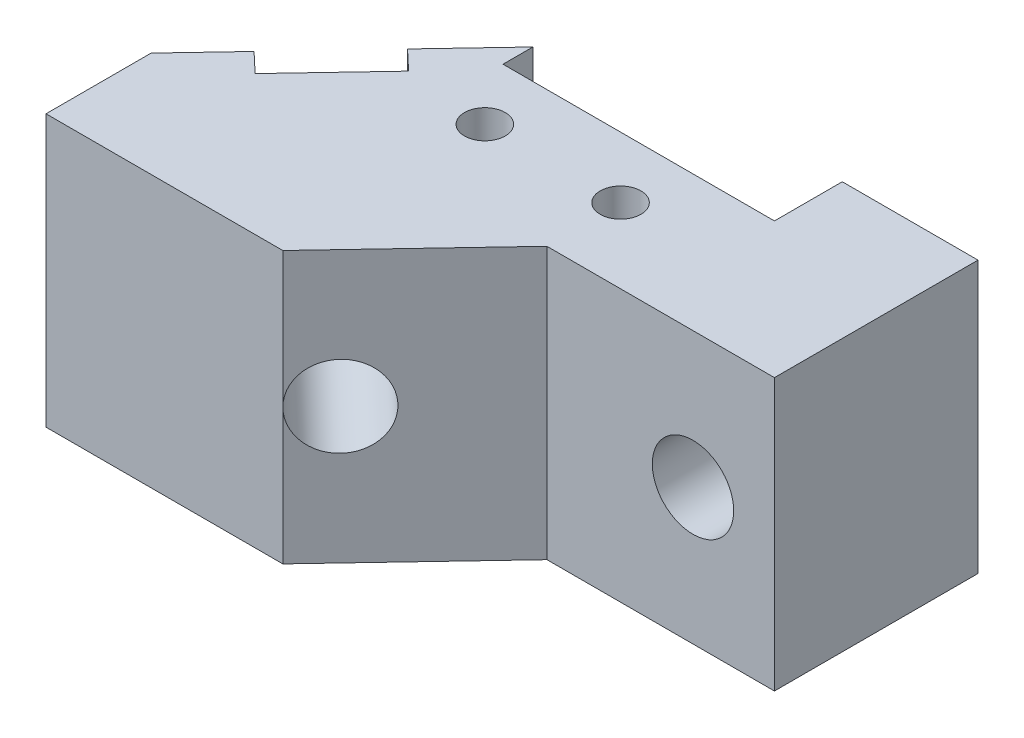
SolidWorks part; units mm, degrees
material "ABS"
ref_plane "Спереди" through (0, 0, 0) normal (0, 0, 1) x (1, 0, 0)
ref_plane "Сверху" through (0, 0, 0) normal (0, 1, 0) x (1, 0, 0)
ref_plane "Справа" through (0, 0, 0) normal (1, 0, 0) x (0, 0, -1)
sketch "Эскиз1" plane through (0, 0, 0) normal (0, 1, 0) x (1, 0, 0)
  line L0 (0, 0) -> (0, 40)
  line L1 (0, 0) -> (-27.6066, 26.1128)
  line L2 (-27.8031, 33.1811) -> (-24.1707, 29.7452)
  line L3 (-27.8031, 33.1811) -> (-34.6749, 25.9162)
  line L4 (-24.1707, 29.7452) -> (-31.0425, 22.4803)
  line L5 (-34.6749, 25.9162) -> (-31.0425, 22.4803)
  line L6 (-3, 40) -> (3, 40)
  line L7 (-3, 40) -> (-3, 25)
  line L8 (3, 40) -> (3, 25)
  line L9 (-3, 25) -> (3, 25)
  line L10 (-27.4886, 21.8718) -> (-23.3656, 26.2307)
  line L11 (-27.4886, 21.8718) -> (-20.2237, 15)
  line L12 (-23.3656, 26.2307) -> (-16.1007, 19.3589)
  line L13 (-20.2237, 15) -> (-16.1007, 19.3589)
  line L14 (-26.4579, 22.9615) -> (7.1963, -8.8716) construction
  line L15 (-37.6749, 55) -> (6, 55)
  line L16 (-37.6749, 55) -> (-37.6749, 15)
  line L17 (-37.6749, 15) -> (6, 15)
  line L18 (6, 55) -> (6, 15)
  line L19 (-24.3963, 25.141) -> (9.2578, -6.6921) construction
  line L20 (34.7394, 2.0647) -> (-36.6641, 2.0647) construction
  line L21 (0, 0) -> (0, -2.0647) construction
  line L22 (-36.6641, -2.0647) -> (34.7394, -2.0647) construction
  point P3 (-27.6066, 26.1128)
  point P7 (0, 25)
  point P12 (-25.4271, 24.0513)
  point P29 (0, 2.0647)
  dimension "D1" = 10
  dimension "D2" = 5
  dimension "D3" = 10
  dimension "laser_dia" = 6
  dimension "D4" = 15
  dimension "D5" = 25
  dimension "D6" = 6
  dimension "D7" = 25
  dimension "D8" = 3
  dimension "D9" = 55
  dimension "D10" = 3
  dimension "D11" = 3
  dimension "D12" = 3
  dimension "D13" = 4.1295
  dimension "D14" = 15
sketch "Эскиз2" plane through (0, 0, 0) normal (0, 1, 0) x (1, 0, 0)
  line L0 (-37.6749, 15) -> (6, 15) construction
  line L1 (-37.6749, 15) -> (-20.2237, 15)
  line L2 (6, 55) -> (6, 15) construction
  line L3 (6, 40) -> (6, 25)
  line L4 (-37.6749, 55) -> (-37.6749, 15) construction
  line L5 (-37.6749, 40) -> (-37.6749, 15)
  line L6 (-3, 40) -> (3, 40) construction
  line L7 (-3, 40) -> (3, 40) construction
  line L8 (-37.6749, 40) -> (6, 40)
  line L10 (-3, 25) -> (3, 25) construction
  line L11 (6, 25) -> (-10.7648, 25)
  line L12 (-10.7648, 25) -> (-20.2237, 15)
  line L14 (-20.2237, 15) -> (-16.1007, 19.3589) construction
extrude "Бобышка-Вытянуть1" add sketch "Эскиз2" along normal blind 20
sketch "Эскиз3" plane through (0, 0, -40) normal (0, 0, -1) x (-1, 0, 0)
  line L0 (0, 0) -> (0, 20) construction
  line L1 (-6, 20) -> (37.6749, 20) construction
  circle A0 centre (0, 10) radius 3
  dimension "D1" = 6
extrude "Вырез-Вытянуть1" cut sketch "Эскиз3" against normal through all
sketch "Эскиз4" plane through (-18.1622, 0, -17.1795) normal (0.7265, 0, 0.6872) x (0.6872, 0, -0.7265)
  line L0 (0, 0) -> (0, 20) construction
  line L1 (-3, 20) -> (10.7648, 20) construction
  circle A0 centre (0, 10) radius 3
  dimension "D1" = 6
extrude "Вырез-Вытянуть2" cut sketch "Эскиз4" against normal up to vertex (13 mm away) up to point (-31.0425, 0, -22.4803)
sketch "Эскиз5" plane through (-27.6066, 0, -26.1128) normal (0.7265, 0, 0.6872) x (0.6872, 0, -0.7265)
  line L1 (5, 5) -> (-5, 5)
  line L2 (5, 5) -> (5, 15)
  line L3 (5, 15) -> (-5, 15)
  line L4 (-5, 5) -> (-5, 15)
  line L5 (5, 5) -> (-5, 15) construction
  line L6 (5, 15) -> (-5, 5) construction
  point P0 (0, 10)
  dimension "D1" = 10
  dimension "D2" = 10
extrude "Вырез-Вытянуть3" cut sketch "Эскиз5" against normal through all
sketch "Эскиз6" plane through (-27.6066, 0, -26.1128) normal (-0.7265, 0, -0.6872) x (-0.6872, 0, 0.7265)
  circle A0 centre (0, 10) radius 3 construction
  circle A1 centre (0, 10) radius 3
  circle A2 centre (0, 10) radius 1
  dimension "D1" = 2
extrude "Бобышка-Вытянуть2" add sketch "Эскиз6" against normal blind 3
ref_plane "sensor_pins" through (-29.786, 0, -28.1743) normal (-0.7265, 0, -0.6872) x (-0.6872, 0, 0.7265)
sketch "Эскиз7" plane through (-29.786, 0, -28.1743) normal (-0.7265, 0, -0.6872) x (-0.6872, 0, 0.7265)
  line L0 (-5, 5) -> (-5, 15) construction
  line L1 (5, 5) -> (-5, 5) construction
  line L2 (5, 15) -> (5, 5) construction
  line L3 (-5, 15) -> (5, 15) construction
  line L4 (-5, 5) -> (-5, 15)
  line L5 (5, 5) -> (-5, 5) construction
  line L6 (5, 15) -> (5, 5)
  line L7 (-5, 15) -> (5, 15) construction
  line L8 (-5, 5) -> (-4, 5)
  line L9 (-4, 5) -> (-4, 0)
  line L11 (-3.1702, 0) -> (14.9921, 0) construction
  line L14 (-3.1702, 0) -> (4, 0)
  line L15 (-4, 0) -> (-3.1702, 0)
  line L16 (4, 5) -> (4, 0)
  line L17 (0, 10) -> (-5, 10) construction
  line L18 (4, 5) -> (5, 5)
  line L19 (4, 15) -> (5, 15)
  line L20 (4, 15) -> (4, 20)
  line L21 (-3.1702, 20) -> (4, 20)
  line L22 (-4, 20) -> (-3.1702, 20)
  line L23 (-4, 15) -> (-4, 20)
  line L24 (-5, 15) -> (-4, 15)
  circle A0 centre (0, 10) radius 1 construction
  circle A1 centre (0, 10) radius 1 construction
  dimension "D1" = 1
  dimension "D2" = 1
extrude "Вырез-Вытянуть4" cut sketch "Эскиз7" along normal through all
sketch "Эскиз8" plane through (0, 0, -40) normal (0, 0, -1) x (-1, 0, 0)
  line L0 (-6, 0) -> (36.4673, 0) construction
  line L1 (4, 0) -> (24, 0)
  line L2 (4, 0) -> (4, 20)
  line L3 (4, 20) -> (24, 20)
  line L4 (24, 0) -> (24, 20)
  line L5 (-6, 20) -> (36.4673, 20) construction
  line L6 (-6, 20) -> (-6, 0) construction
  line L7 (35.0121, 5) -> (35.0121, 15) construction
  line L8 (24, 7.5) -> (35.0121, 7.5)
  line L9 (24, 7.5) -> (24, 12.5)
  line L10 (24, 12.5) -> (35.0121, 12.5)
  line L11 (35.0121, 7.5) -> (35.0121, 12.5)
  point P16 (24, 10)
  point P17 (24, 10)
  line M8 (35.0121, 5) -> (35.0121, 15)
  line M11 (36.4673, 20) -> (-6, 20)
  line M13 (-6, 0) -> (36.4673, 0)
  dimension "D1" = 20
  dimension "D2" = 10
  dimension "D3" = 5
extrude "Вырез-Вытянуть5" cut sketch "Эскиз8" against normal blind 5 contours L10 L4 L8 M8 | L4 L2 M13 M11
sketch "Эскиз9" plane through (0, 20, 0) normal (0, 1, 0) x (1, 0, 0)
  line L0 (-27.8031, 33.1811) -> (-34.6749, 25.9162) construction
  line L1 (-27.8031, 33.1811) -> (-34.6749, 25.9162) construction
  line L2 (-24, 37.2018) -> (-37.6749, 22.7446)
  line L3 (-24, 35) -> (-24, 40) construction
  line L4 (-37.6749, 30.1304) -> (-37.6749, 15) construction
  line L5 (-24, 37.2018) -> (-24, 40)
  line L6 (-24, 40) -> (-37.6749, 40)
  line L7 (-37.6749, 40) -> (-37.6749, 22.7446)
extrude "Вырез-Вытянуть6" cut sketch "Эскиз9" against normal through all
sketch "Эскиз10" plane through (0, 20, 0) normal (0, 1, 0) x (1, 0, 0)
  line L0 (-37.6749, 15) -> (6, 15) construction
  line L1 (-37.6749, 15) -> (6, 15) construction
  line L2 (-15.8374, 15) -> (-15.8374, 53.3164) construction
  line L3 (-24, 35) -> (-4, 35) construction
  circle A0 centre (-10.8374, 30.5) radius 1.5
  circle A1 centre (-20.8374, 30.5) radius 1.5
  dimension "D1" = 3
  dimension "D2" = 4.5
  dimension "D3" = 10
extrude "Вырез-Вытянуть7" cut sketch "Эскиз10" against normal through all
equation "\"laser_body_h\"= 15"
equation "\"laser_body_dia\"= 6"
equation "\"laser_dia@Эскиз1\"=\"laser_body_dia\""
equation "\"D4@Эскиз1\"=\"laser_body_h\""
equation "\"laser_Focus\"= 25"
equation "\"D5@Эскиз1\"=\"laser_Focus\""
equation "\"sens_lens_body_h\"= 10"
equation "\"D3@Эскиз1\"=\"sens_lens_body_h\""
equation "\"sens_lens_body_dia\"= 6"
equation "\"D6@Эскиз1\"=\"sens_lens_body_dia\""
equation "\"sensor_to_lens_space\"= 3"
equation "\"D8@Эскиз1\"=\"sensor_to_lens_space\""
equation "\"sersor_Focus\"= 25"
equation "\"D7@Эскиз1\"=\"sersor_Focus\""
equation "\"min_wall\"=3"
equation "\"D10@Эскиз1\"=\"min_wall\""
equation "\"D11@Эскиз1\"=\"min_wall\""
equation "\"distance_focus_to_lower_side\"= 15"
equation "\"D14@Эскиз1\"=\"distance_focus_to_lower_side\""
equation "\"extruder_to_nozzle_h\"= 50"
equation "\"bed_to_nozzle_h\"= 5"
equation "\"D9@Эскиз1\"=\"extruder_to_nozzle_h\"+\"bed_to_nozzle_h\""
equation "\"D1@Эскиз3\"=\"laser_body_dia\""
equation "\"D1@Эскиз4\"=\"sens_lens_body_dia\""
equation "\"D1@Бобышка-Вытянуть2\"=\"sensor_to_lens_space\""
equation "\"D2@Эскиз10\"=\"min_wall\"+1.5"
